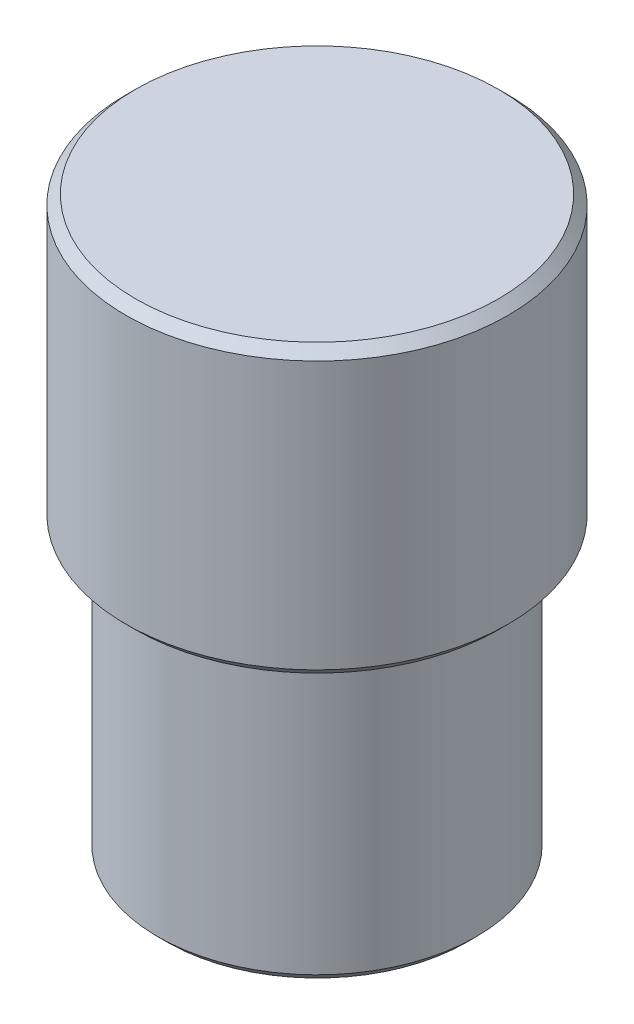
SolidWorks part; units mm, degrees
material "303"
ref_plane "前视" through (0, 0, 0) normal (0, 0, 1) x (1, 0, 0)
ref_plane "上视" through (0, 0, 0) normal (0, 1, 0) x (1, 0, 0)
ref_plane "右视" through (0, 0, 0) normal (1, 0, 0) x (0, 0, -1)
sketch "草图1" plane through (0, 0, 0) normal (0, 0, 1) x (1, 0, 0)
  line L0 (0, -1000) -> (0, 49000) construction
  line L1 (0, 0) -> (5, 0)
  line L2 (5, 0) -> (5, 9)
  line L3 (5, 9) -> (6, 9)
  line L4 (6, 9) -> (6, 18)
  line L5 (6, 18) -> (0, 18)
  line L6 (0, 18) -> (0, 0)
  dimension "D1" = 12
  dimension "D2" = 10
  dimension "D3" = 18
  dimension "D4" = 9
revolve "旋转1" add sketch "草图1" angle 360 about L0
chamfer "倒角1" distance 0.3 angle 45 3 edges at (5, 0, 0) (6, 18, 0) (6, 9, 0)
